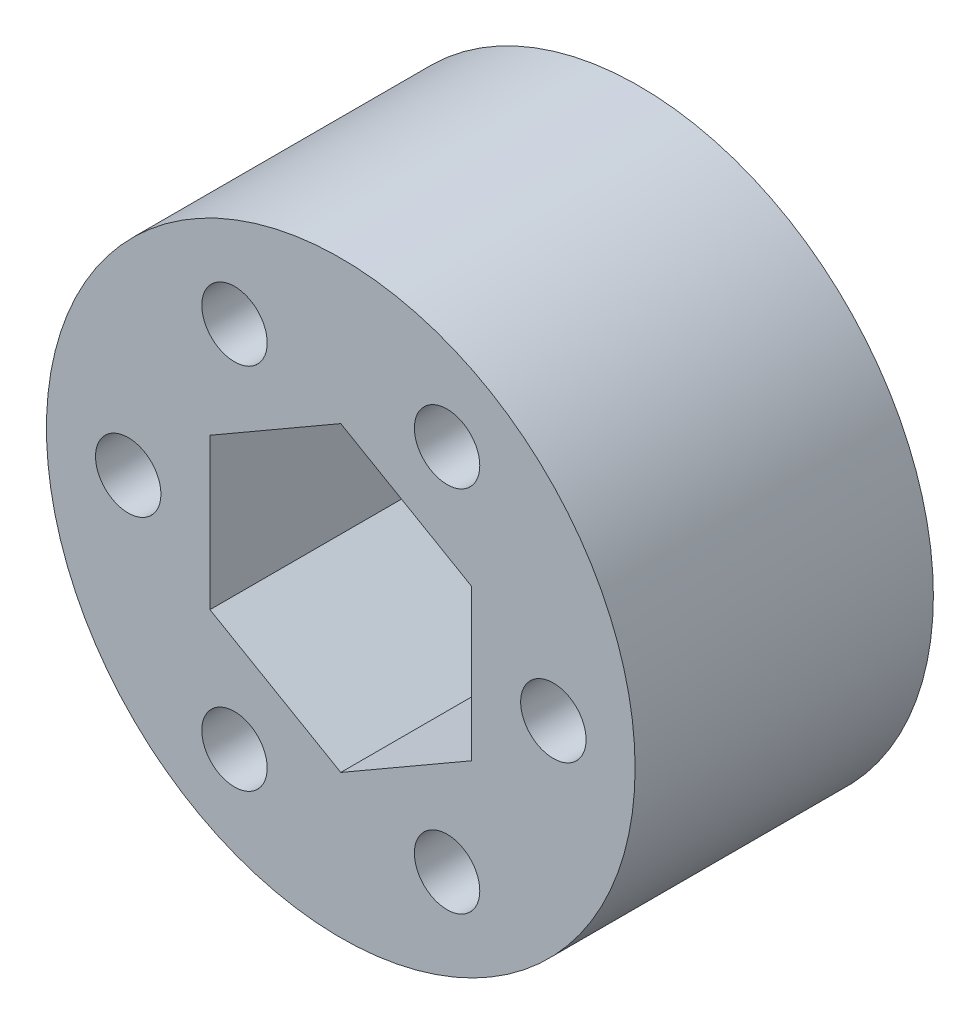
SolidWorks part; units mm, degrees
material "PP Homopolymer"
ref_plane "Front Plane" through (0, 0, 0) normal (0, 0, 1) x (1, 0, 0)
ref_plane "Top Plane" through (0, 0, 0) normal (0, 1, 0) x (1, 0, 0)
ref_plane "Right Plane" through (0, 0, 0) normal (1, 0, 0) x (0, 0, -1)
sketch "Sketch1" plane through (0, 0, 0) normal (0, 0, 1) x (1, 0, 0)
  circle A0 centre (0, 0) radius 14.2875
  dimension "D1" = 28.575
extrude "Boss-Extrude1" add sketch "Sketch1" along normal mid plane 14.478
sketch "Sketch2" plane through (0, 0, 7.239) normal (0, 0, 1) x (1, 0, 0)
  line L0 (0, 7.3323) -> (-6.35, 3.6662)
  line L1 (-6.35, 3.6662) -> (-6.35, -3.6662)
  line L2 (-6.35, -3.6662) -> (0, -7.3323)
  line L3 (0, -7.3323) -> (6.35, -3.6662)
  line L4 (6.35, -3.6662) -> (6.35, 3.6662)
  line L5 (6.35, 3.6662) -> (0, 7.3323)
  circle A0 centre (-10.3187, 0) radius 1.5875
  circle A1 centre (-5.1594, 8.9363) radius 1.5875
  circle A2 centre (5.1594, 8.9363) radius 1.5875
  circle A3 centre (10.3187, 0) radius 1.5875
  circle A4 centre (5.1594, -8.9363) radius 1.5875
  circle A5 centre (-5.1594, -8.9363) radius 1.5875
  point P6 (0, 0)
  point P7 (6.35, 0)
  point P9 (-6.35, 0)
  point P24 (0, 0)
  dimension "D3" = 3.175
  dimension "D4" = 10.3187
  dimension "D1" = 12.7
  dimension "D2" = 12.7
  dimension "D5" = 6
extrude "Cut-Extrude1" cut sketch "Sketch2" against normal through all
